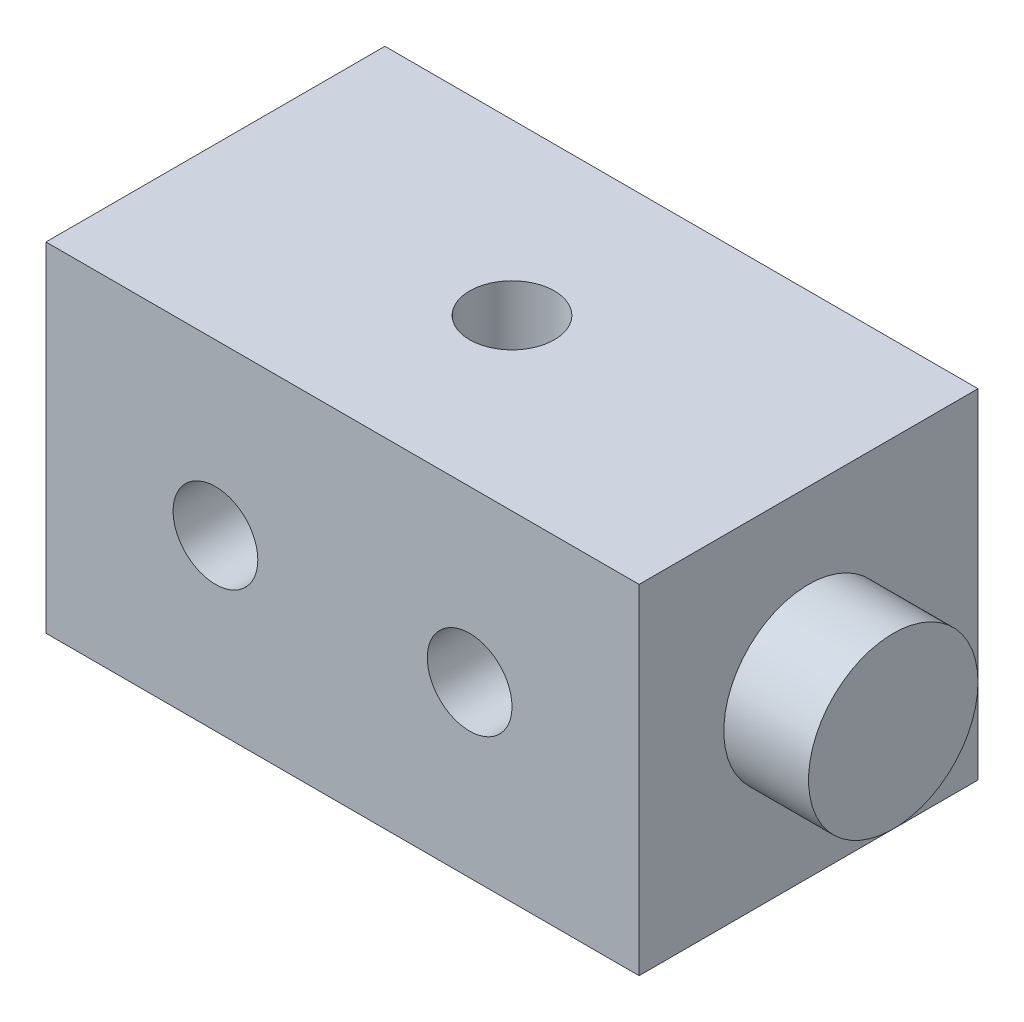
SolidWorks part; units mm, degrees
material "Delrin 2700 NC010, Low Viscosity Acetal Copolymer (SS)"
ref_plane "Front Plane" through (0, 0, 0) normal (0, 0, 1) x (1, 0, 0)
ref_plane "Top Plane" through (0, 0, 0) normal (0, 1, 0) x (1, 0, 0)
ref_plane "Right Plane" through (0, 0, 0) normal (1, 0, 0) x (0, 0, -1)
sketch "Sketch1" plane through (0, 0, 0) normal (0, 0, 1) x (1, 0, 0)
  line L0 (0, 12.7) -> (44.45, 12.7) construction
  line L1 (0, 0) -> (44.45, 0)
  line L2 (0, 0) -> (0, 25.4)
  line L3 (0, 25.4) -> (44.45, 25.4)
  line L4 (44.45, 0) -> (44.45, 25.4)
  circle A0 centre (12.7, 12.7) radius 3.175
  circle A1 centre (31.75, 12.7) radius 3.175
  dimension "D2" = 12.7
  dimension "D3" = 6.35
  dimension "D1" = 25.4
  dimension "D4" = 19.05
  dimension "D5" = 12.7
extrude "Boss-Extrude1" add sketch "Sketch1" along normal blind 25.4
sketch "Sketch2" plane through (44.45, 0, 0) normal (1, 0, 0) x (0, 0, -1)
  line L1 (-25.4, 25.4) -> (0, 25.4) construction
  line L2 (-25.4, 25.4) -> (-25.4, 0) construction
  line L3 (-25.4, 0) -> (0, 0) construction
  line L4 (0, 25.4) -> (0, 0) construction
  line L5 (-25.4, 25.4) -> (0, 0) construction
  line L6 (-25.4, 0) -> (0, 25.4) construction
  circle A0 centre (-12.7, 12.7) radius 6.35
  point P4 (-12.7, 12.7)
  dimension "D1" = 12.7
extrude "Boss-Extrude2" add sketch "Sketch2" along normal blind 6.35
sketch "Sketch3" plane through (0, 25.4, 0) normal (0, 1, 0) x (1, 0, 0)
  line L0 (44.45, -12.7) -> (0, -12.7) construction
  line L1 (44.45, -25.4) -> (44.45, 0) construction
  line L2 (0, -25.4) -> (0, 0) construction
  circle A0 centre (22.225, -12.7) radius 3.175
  point P8 (22.7854, -12.7)
  dimension "D1" = 22.225
  dimension "D2" = 6.35
extrude "Cut-Extrude1" cut sketch "Sketch3" against normal through all
